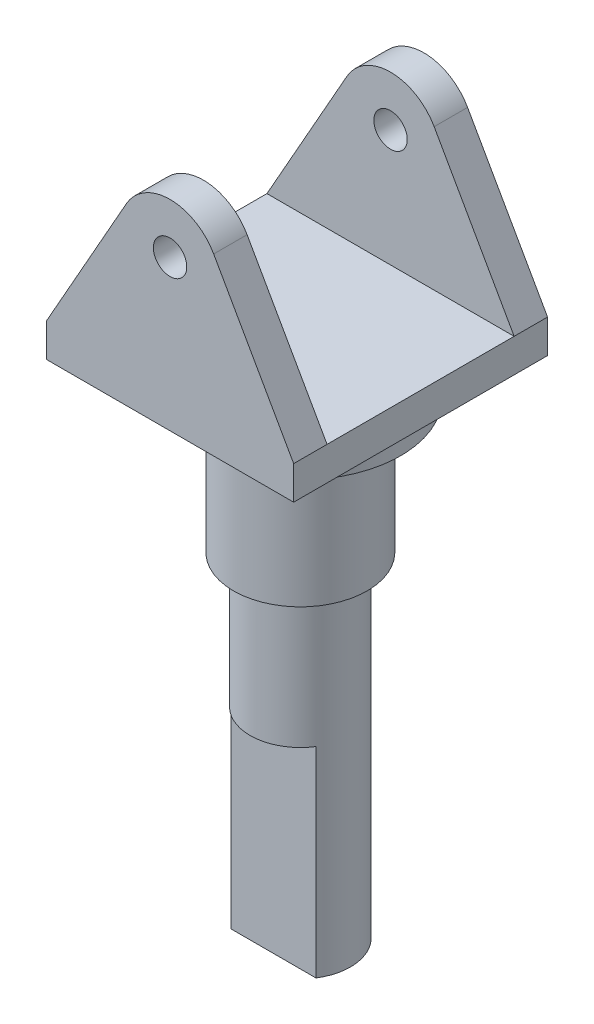
SolidWorks part; units mm, degrees
ref_plane "Front Plane" through (0, 0, 0) normal (0, 0, 1) x (1, 0, 0)
ref_plane "Top Plane" through (0, 0, 0) normal (0, 1, 0) x (1, 0, 0)
ref_plane "Right Plane" through (0, 0, 0) normal (1, 0, 0) x (0, 0, -1)
sketch "Sketch1" plane through (0, 0, 0) normal (0, 0, 1) x (1, 0, 0)
  line L0 (0, 0) -> (0, 53614.8937) construction
  line L1 (0, 0) -> (53614.8937, 0) construction
  line L2 (0, 0) -> (0, 10)
  line L3 (0, 0) -> (74.0003, 0)
  line L4 (74.0003, 0) -> (74.0003, 10)
  line L5 (74.0003, 10) -> (50.0601, 52.3779)
  line L6 (0, 10) -> (23.9399, 52.3779)
  circle A0 centre (37, 45) radius 5
  arc A1 (50.0601, 52.3779) -> (23.9399, 52.3779) centre (37, 45) ccw
  dimension "D1" = 10
  dimension "D2" = 30
  dimension "D3" = 37
  dimension "D4" = 10
  dimension "D5" = 45
  dimension "D6" = 10
  dimension "D7" = 37.0003
extrude "Boss-Extrude1" add sketch "Sketch1" against normal blind 76
sketch "Sketch2" plane through (0, 0, 0) normal (1, 0, 0) x (0, 0, -1)
  line L0 (10, 61.0487) -> (10, 10)
  line L1 (76, 10) -> (0, 10) construction
  line L2 (10, 10) -> (66, 10)
  line L3 (66, 10) -> (66, 61.0487)
  line L4 (66, 61.0487) -> (10, 61.0487)
  line L5 (76, 10) -> (76, 52.3779) construction
  dimension "D1" = 56
  dimension "D2" = 10
extrude "Cut-Extrude1" cut sketch "Sketch2" along normal blind 128
ref_plane "Plane1" through (38, 0, 0) normal (-1, 0, 0) x (0, 0, 1)
sketch "Sketch6" plane through (38, 0, 0) normal (-1, 0, 0) x (0, 0, 1)
  line L0 (-38, 0) -> (-38, -115.7491) construction
  line L1 (-76, 0) -> (0, 0) construction
  line L3 (-18, -10) -> (-8, -10)
  line L4 (-8, -10) -> (-8, 0)
  line L5 (-8, 0) -> (-38, 0)
  line L7 (-23, -50) -> (-18, -50)
  line L8 (-18, -50) -> (-18, -10)
  line L9 (-23, -50) -> (-23, -150)
  line L10 (-23, -150) -> (-38, -150)
  line L11 (-38, -150) -> (-38, 0)
  dimension "D1" = 20
  dimension "D2" = 15
  dimension "D3" = 30
  dimension "D4" = 10
  dimension "D5" = 40
  dimension "D6" = 100
revolve "Revolve2" add sketch "Sketch6" angle 360 about L0
sketch "Sketch8" plane through (0, -10, 0) normal (0, -1, 0) x (1, 0, 0)
  line L0 (8, -38) -> (68, -38) construction
  line L1 (20, -14) -> (56, -14)
  line L2 (20, -62) -> (56, -62)
  circle A0 centre (38, -38) radius 30 construction
  circle A1 centre (38, -38) radius 30 construction
  circle A2 centre (38, -38) radius 30
  circle M4 centre (38, -38) radius 30
  dimension "D1" = 24
  dimension "D2" = 24
extrude "Cut-Extrude2" cut sketch "Sketch8" against normal blind 10 contours L2 M4 | L1 M4
sketch "Sketch9" plane through (0, -150, 0) normal (0, -1, 0) x (1, 0, 0)
  line L0 (25.3114, -30) -> (50.6886, -30)
  line L2 (23, -38) -> (53, -38) construction
  circle A0 centre (38, -38) radius 15
  circle M4 centre (38, -38) radius 15
  dimension "D2" = 30
  dimension "D1" = 8
extrude "Cut-Extrude3" cut sketch "Sketch9" against normal blind 60 contours L0 M4
